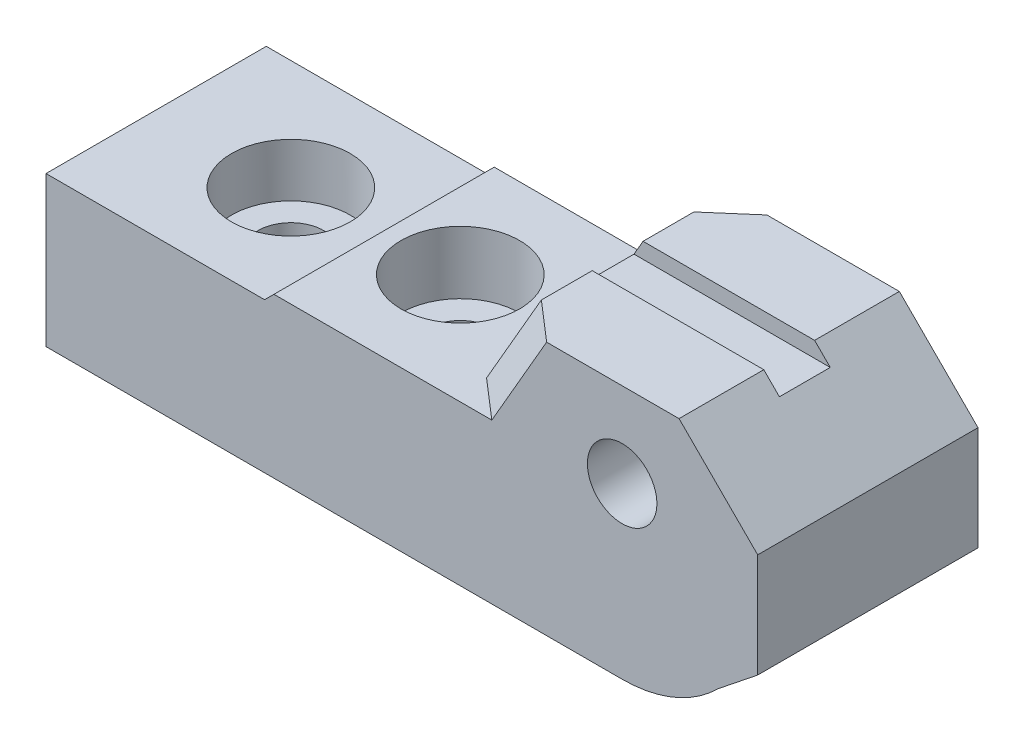
SolidWorks part; units mm, degrees
ref_plane "정면" through (0, 0, 0) normal (0, 0, 1) x (1, 0, 0)
ref_plane "윗면" through (0, 0, 0) normal (0, 1, 0) x (1, 0, 0)
ref_plane "우측면" through (0, 0, 0) normal (1, 0, 0) x (0, 0, -1)
sketch "스케치1" plane through (0, 0, 0) normal (0, 0, 1) x (1, 0, 0)
  line L0 (24, 9.4) -> (27.2332, 15)
  line L1 (0, 0) -> (34, 0)
  line L2 (0, 0) -> (0, 8.847)
  line L3 (13.4517, 9.4) -> (24, 9.4)
  line L4 (42, 8) -> (42, 10.3582)
  line L5 (27.2332, 15) -> (37.3582, 15)
  line L6 (37.3582, 15) -> (42, 10.3582)
  line L7 (34, 10) -> (34, 0) construction
  line L8 (42, 8) -> (42, 4.2146)
  line L9 (39.6569, 2.3431) -> (42, 4.2146)
  line L10 (0, 8.847) -> (12.8988, 8.847)
  line L11 (12.8988, 8.847) -> (13.4517, 9.4)
  circle A0 centre (34, 10) radius 2.05
  arc A1 (39.6569, 2.3431) -> (34, 0) centre (34, 8) cw
  dimension "D3" = 4.1
  dimension "D1" = 120
  dimension "D2" = 9.4
  dimension "D4" = 34
  dimension "D5" = 10
  dimension "D6" = 42
  dimension "D7" = 15
  dimension "D8" = 135
  dimension "D9" = 24
extrude "보스-돌출1" add sketch "스케치1" along normal mid plane 13
sketch "스케치2" plane through (0, 0, 0) normal (0, 1, 0) x (1, 0, 0)
  line L0 (7.95, 0) -> (0, 0) construction
  line L1 (7.95, 0) -> (17.95, 0) construction
  circle A0 centre (7.95, 0) radius 1.925
  circle A1 centre (17.95, 0) radius 1.925
  dimension "D1" = 3.85
  dimension "D2" = 3.85
  dimension "D3" = 10
  dimension "D4" = 7.95
extrude "컷-돌출1" cut sketch "스케치2" along normal through all
sketch "스케치4" plane through (0, 9.4, 0) normal (0, 1, 0) x (1, 0, 0)
  circle A0 centre (7.95, 0) radius 3.5
  circle A1 centre (17.95, 0) radius 3.5
  dimension "D1" = 7
  dimension "D2" = 7
extrude "컷-돌출3" cut sketch "스케치4" against normal blind 3.7
sketch "스케치5" plane through (0, 0, 0) normal (0, 0, 1) x (1, 0, 0)
  line L1 (22.5538, 18.2756) -> (40.8629, 18.2756)
  line L2 (22.5538, 18.2756) -> (22.5538, 14.0771)
  line L3 (22.5538, 14.0771) -> (40.8629, 14.0771)
  line L4 (40.8629, 18.2756) -> (40.8629, 14.0771)
extrude "컷-돌출4" cut sketch "스케치5" against normal mid plane 3
chamfer "모따기1" distance 2 angle 45 2 edges at (25.6166, 12.2, -6.5) (25.6166, 12.2, 6.5)
